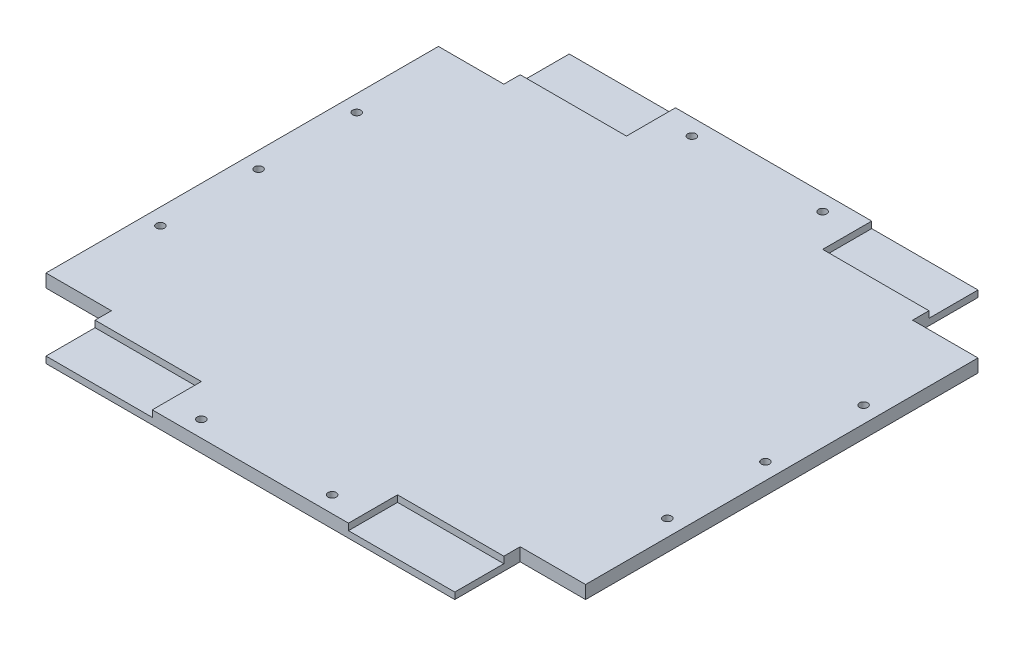
SolidWorks part; units mm, degrees
material "Oak"
ref_plane "Front Plane" through (0, 0, 0) normal (0, 0, 1) x (1, 0, 0)
ref_plane "Top Plane" through (0, 0, 0) normal (0, 1, 0) x (1, 0, 0)
ref_plane "Right Plane" through (0, 0, 0) normal (1, 0, 0) x (0, 0, -1)
sketch "Sketch1" plane through (0, 0, 0) normal (0, 1, 0) x (1, 0, 0)
  line L0 (125, 160) -> (-125, 160)
  line L1 (-125, 160) -> (-125, 120)
  line L2 (-125, 120) -> (-165, 120)
  line L3 (-165, 120) -> (-165, -120)
  line L4 (0, 0) -> (0, 160) construction
  line L5 (0, 0) -> (-165, 0) construction
  line L6 (165, 120) -> (165, -120)
  line L7 (125, 120) -> (165, 120)
  line L8 (125, 160) -> (125, 120)
  line L9 (125, -160) -> (125, -120)
  line L10 (125, -120) -> (165, -120)
  line L11 (-125, -120) -> (-165, -120)
  line L12 (-125, -160) -> (-125, -120)
  line L13 (125, -160) -> (-125, -160)
  point P13 (165, 0)
  dimension "D1" = 165
  dimension "D2" = 160
  dimension "D3" = 40
  dimension "D4" = 40
extrude "Boss-Extrude1" add sketch "Sketch1" along normal blind 8
sketch "Sketch2" plane through (0, 8, 0) normal (0, 1, 0) x (1, 0, 0)
  line L0 (0, 0) -> (0, -160) construction
  line L1 (-125, -160) -> (125, -160) construction
  line L2 (165, 120) -> (125, 120) construction
  line L3 (165, -120) -> (165, 120) construction
  line L6 (0, 0) -> (165, 0) construction
  circle A0 centre (155, 60) radius 2.5
  circle A1 centre (155, 0) radius 2.5
  circle A2 centre (155, -60) radius 2.5
  circle A12 centre (40, -150) radius 2.5
  circle A13 centre (-40, -150) radius 2.5
  circle A16 centre (-155, -60) radius 2.5
  circle A17 centre (-155, 0) radius 2.5
  circle A18 centre (-155, 60) radius 2.5
  circle A19 centre (-40, 150) radius 2.5
  circle A20 centre (40, 150) radius 2.5
  point P26 (0, 0)
  dimension "D1" = 5
  dimension "D2" = 5
  dimension "D3" = 5
  dimension "D8" = 5
  dimension "D9" = 5
  dimension "D10" = 40
  dimension "D4" = 60
  dimension "D5" = 60
  dimension "D6" = 60
  dimension "D7" = 10
  dimension "D11" = 40
  dimension "D12" = 10
  dimension "D13" = 10
extrude "Cut-Extrude1" cut sketch "Sketch2" against normal up to surface (8 mm away) up to face at (0, 0, 0)
sketch "Sketch3" plane through (0, 8, 0) normal (0, 1, 0) x (1, 0, 0)
  line L0 (125, 160) -> (-125, 160) construction
  line L1 (-60, 160) -> (-125, 160)
  line L2 (-60, 160) -> (-60, 130)
  line L3 (-60, 130) -> (-125, 130)
  line L4 (-125, 160) -> (-125, 130)
  line L5 (-125, 160) -> (-125, 120) construction
  dimension "D1" = 30
  dimension "D2" = 65
extrude "Cut-Extrude2" cut sketch "Sketch3" against normal blind 4
ref_plane "Plane1" through (0, 0, 0) normal (0, 0, -1) x (-1, 0, 0)
ref_plane "Plane2" through (0, 0, 0) normal (-1, 0, 0) x (0, 0, 1)
mirror "Mirror1" about plane through (0, 0, 0) normal (0, 0, -1) of "Cut-Extrude2"
mirror "Mirror2" about plane through (0, 0, 0) normal (-1, 0, 0) of "Mirror1", "Cut-Extrude2"
